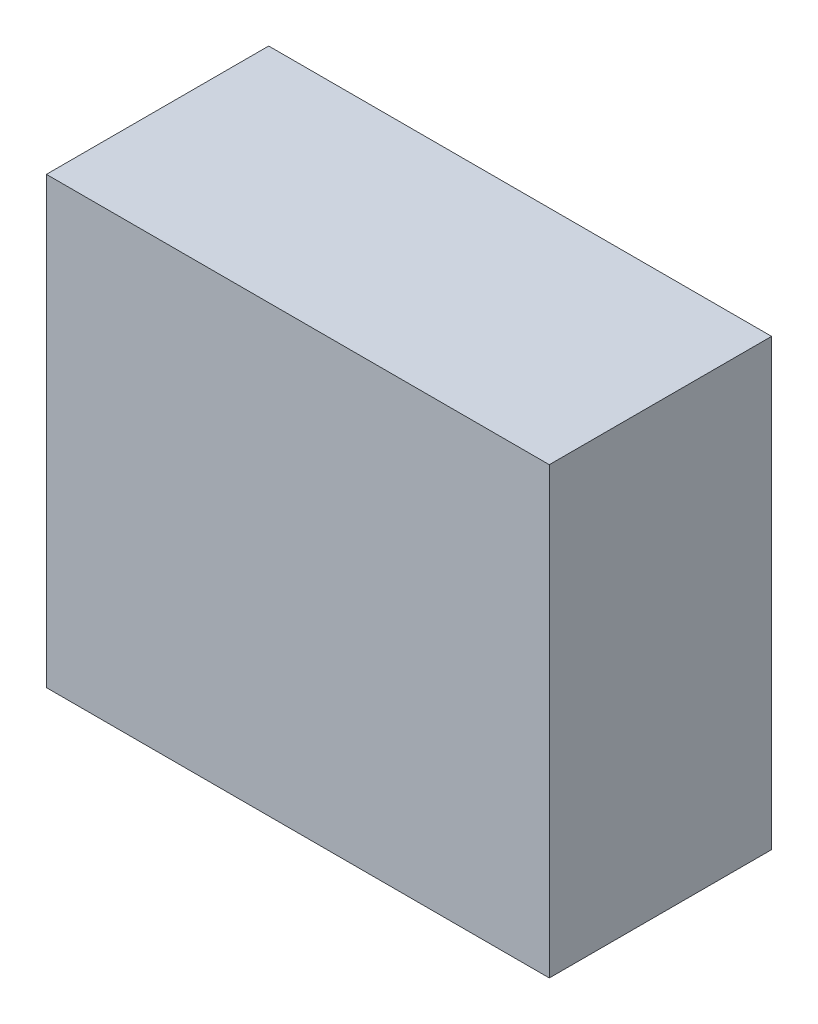
SolidWorks part; units mm, degrees
material "Rubber"
ref_plane "Front Plane" through (0, 0, 0) normal (0, 0, 1) x (1, 0, 0)
ref_plane "Top Plane" through (0, 0, 0) normal (0, 1, 0) x (1, 0, 0)
ref_plane "Right Plane" through (0, 0, 0) normal (1, 0, 0) x (0, 0, -1)
sketch "Sketch1" plane through (0, 0, 0) normal (0, 1, 0) x (1, 0, 0)
  line L1 (0, 0) -> (18.1, 0)
  line L2 (0, 0) -> (0, -8)
  line L3 (0, -8) -> (18.1, -8)
  line L4 (18.1, 0) -> (18.1, -8)
  dimension "D1" = 8
  dimension "D2" = 18.1
extrude "Boss-Extrude1" add sketch "Sketch1" along normal blind 16
